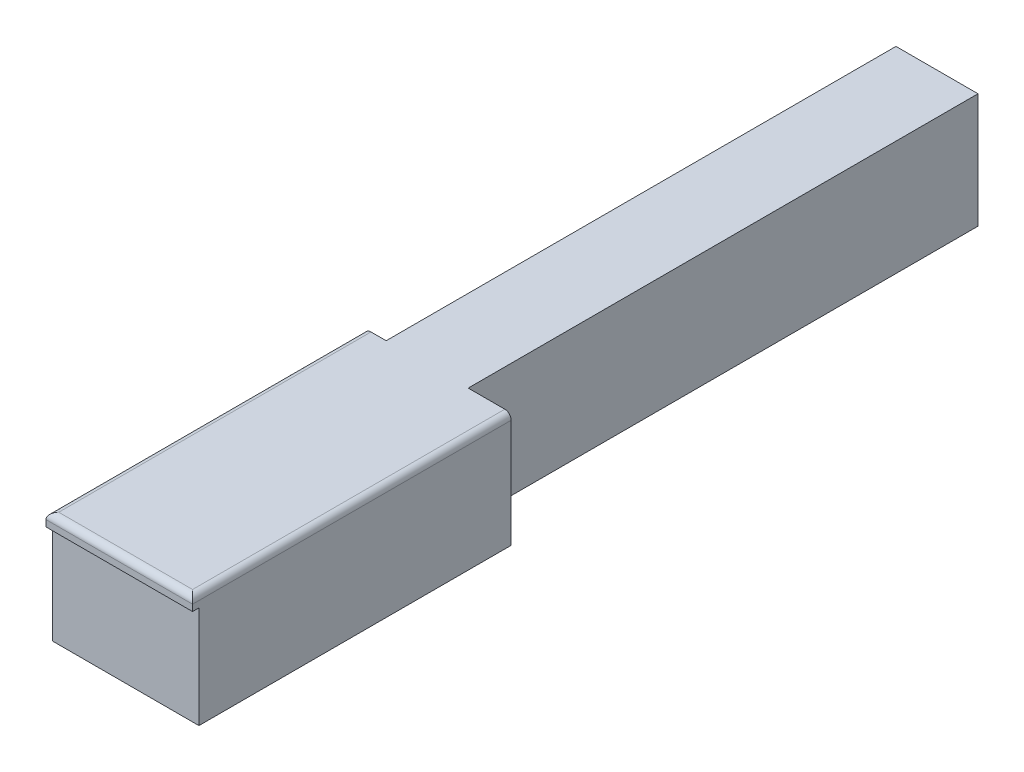
SolidWorks part; units mm, degrees
material "Pino"
ref_plane "Alzado" through (0, 0, 0) normal (0, 0, 1) x (1, 0, 0)
ref_plane "Planta" through (0, 0, 0) normal (0, 1, 0) x (1, 0, 0)
ref_plane "Vista lateral" through (0, 0, 0) normal (1, 0, 0) x (0, 0, -1)
sketch "Croquis2" plane through (0, 0, 0) normal (0, 1, 0) x (1, 0, 0)
  line L1 (0, 0) -> (23, 0)
  line L2 (0, 0) -> (0, 130)
  line L3 (0, 130) -> (23, 130)
  line L4 (23, 0) -> (23, 130)
  line L5 (0, 130) -> (3.38, 130)
  line L6 (0, 115.866) -> (0, 50)
  line L7 (23, 50) -> (16.255, 50)
  line L8 (16.255, 130) -> (16.255, 50)
  line L9 (0, 50) -> (3.38, 50)
  line L10 (0, 130) -> (0, 50)
  line L11 (0, 50) -> (3.38, 50)
  line L12 (3.38, 130) -> (3.38, 50)
  dimension "D1" = 23
  dimension "D2" = 130
  dimension "D3" = 50
  dimension "D4" = 12.875
  dimension "D5" = 3.38
extrude "Saliente-Extruir1" add sketch "Croquis2" along normal blind 18 contours L8 L3 L2 L1 L4 L7
sketch "Croquis3" plane through (0, 0, 0) normal (0, 0, 1) x (1, 0, 0)
  line L0 (23, 18) -> (23, 0) construction
  line L1 (0, 0) -> (23, 0)
  line L2 (0, 0) -> (0, 16)
  line L3 (0, 16) -> (23, 16)
  line L4 (23, 0) -> (23, 16)
extrude "Cortar-Extruir1" cut sketch "Croquis3" against normal blind 1
fillet "Redondeo1" radius 1 3 edges at (11.5, 18, 0) (23, 18, -25) (0, 18, -25)
